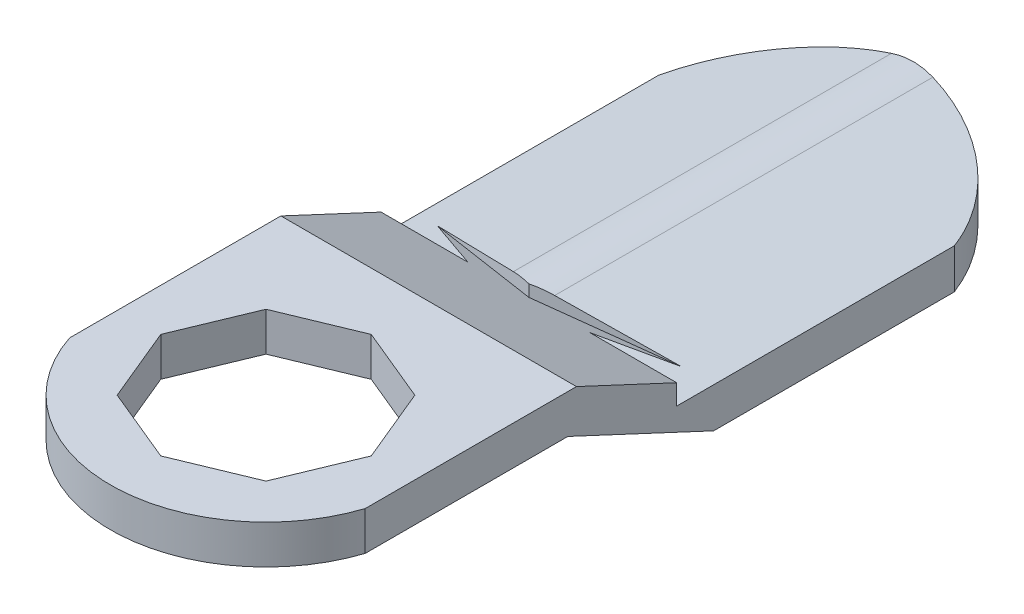
SolidWorks part; units mm, degrees
ref_plane "前视基准面" through (0, 0, 0) normal (0, 0, 1) x (1, 0, 0)
ref_plane "上视基准面" through (0, 0, 0) normal (0, 1, 0) x (1, 0, 0)
ref_plane "右视基准面" through (0, 0, 0) normal (1, 0, 0) x (0, 0, -1)
sketch "草图1" plane through (0, 0, 0) normal (0, 1, 0) x (1, 0, 0)
  line L0 (0, 33.2521) -> (0, -38.6616) construction
  line L1 (-19.8522, 0) -> (15.9092, 0) construction
  line L2 (0, 5.412) -> (-3.8268, 3.8268)
  line L3 (-3.8268, 3.8268) -> (-5.412, 0)
  line L4 (-5.412, 0) -> (-3.8268, -3.8268)
  line L5 (-3.8268, -3.8268) -> (0, -5.412)
  line L6 (0, -5.412) -> (3.8268, -3.8268)
  line L7 (3.8268, -3.8268) -> (5.412, 0)
  line L8 (5.412, 0) -> (3.8268, 3.8268)
  line L9 (3.8268, 3.8268) -> (0, 5.412)
  line L10 (-7.6, -2.498) -> (-7.6, 7.9206)
  line L11 (7.6, -2.498) -> (7.6, 7.9206)
  line L12 (-12.2442, -8) -> (14.4757, -8) construction
  line L13 (-14.231, 9.5) -> (17.6054, 9.5) construction
  circle A0 centre (0, 0) radius 5 construction
  arc A1 (7.6, -2.498) -> (-7.6, -2.498) centre (0, 0) cw
  arc A2 (7.6, 7.9206) -> (-7.6, 7.9206) centre (0, -9.5756) ccw
  dimension "D1" = 10
  dimension "D3" = 8
  dimension "D2" = 15.2
  dimension "D4" = 17.5
extrude "凸台-拉伸1" add sketch "草图1" along normal blind 2
sketch "草图3" plane through (0, 2, 0) normal (0, 1, 0) x (1, 0, 0)
  line L0 (-7.6, 7.9206) -> (-7.6, 15.4206)
  line L1 (-7.6, 15.4206) -> (0, 13.5178)
  line L2 (0, -2.2394) -> (0, 20.3405) construction
  line L3 (7.6, 15.4206) -> (0, 13.5178)
  line L4 (7.6, 7.9206) -> (7.6, 15.4206)
  arc A0 (7.6, 7.9206) -> (-7.6, 7.9206) centre (0, -9.5756) ccw construction
  arc A1 (7.6, 7.9206) -> (-7.6, 7.9206) centre (0, -9.5756) ccw
  dimension "D1" = 7.5
extrude "凸台-拉伸2" add sketch "草图3" against normal blind 8
sketch "草图4" plane through (7.6, 0, 0) normal (1, 0, 0) x (0, 0, -1)
  line L0 (8.3643, 2) -> (15.4206, -1.2929)
  line L1 (-2.498, 2) -> (15.4206, 2) construction
  line L3 (15.4206, -1.2929) -> (15.4206, -3.5)
  line L4 (15.4206, -3.5) -> (7.9206, 0)
  line L5 (15.4206, -6) -> (15.4206, 2) construction
  dimension "D1" = 2
  dimension "D2" = 5.5
extrude "切除-拉伸1" cut sketch "草图4" against normal through all and the other way through all
sketch "草图5" plane through (0, 2, 0) normal (0, 1, 0) x (1, 0, 0)
  line L0 (-7.6, 15.4206) -> (-7.6, 27.798)
  line L1 (-18.4795, 14.2131) -> (16.9599, 14.2131) construction
  line L2 (0, -10.618) -> (0, 36.9986) construction
  line L3 (-13.3383, 33.3) -> (9.3441, 33.3) construction
  line L4 (-16.4955, -8) -> (13.444, -8) construction
  line L5 (7.6, 15.4206) -> (7.6, 27.798)
  line L6 (-7.6, 15.4206) -> (0, 13.5178) construction
  line L7 (0, 13.5178) -> (7.6, 15.4206) construction
  line L8 (-7.6, 15.4206) -> (0, 13.5178)
  line L9 (0, 13.5178) -> (7.6, 15.4206)
  arc A0 (7.6, 27.798) -> (-7.6, 27.798) centre (0, 25.3) ccw
  arc A1 (-7.6, -2.498) -> (7.6, -2.498) centre (0, 0) ccw construction
  dimension "D1" = 41.3
extrude "凸台-拉伸3" add sketch "草图5" against normal up to vertex (5.5 mm away) up to point (7.6, -3.5, -15.4206)
ref_plane "基准面1" through (0, 0, -35) normal (0, 0, 1) x (1, 0, 0)
sketch "草图6" plane through (0, 0, -35) normal (0, 0, 1) x (1, 0, 0)
  line L0 (0, 4.0634) -> (0, -5.1191) construction
  line L1 (7.6, -1.4464) -> (1.0627, 0.0778)
  line L2 (9.4559, 0.2) -> (-12.5549, 0.2) construction
  line L4 (7.6, -3.5) -> (7.6, 2) construction
  line L5 (-7.6, -1.4464) -> (-1.0627, 0.0778)
  line L6 (7.6, -3.5) -> (0.6085, -1.87)
  line L7 (-7.6, -3.5) -> (-0.6085, -1.87)
  line L8 (7.2025, -3.4073) -> (0.6085, -1.87) construction
  line L9 (-7.1459, -3.3941) -> (-0.6085, -1.87) construction
  line L10 (-7.6, -3.5) -> (-7.6, 2) construction
  line L11 (-7.6, -3.5) -> (7.6, -3.5) construction
  line L12 (7.6566, -1.4596) -> (1.0627, 0.0778) construction
  line L13 (7.6, -1.4464) -> (7.6, -3.5)
  line L14 (-7.6, -1.4464) -> (-7.6, -3.5)
  arc A0 (1.0627, 0.0778) -> (-1.0627, 0.0778) centre (0, -4.4802) ccw
  arc A1 (0.6085, -1.87) -> (-0.6085, -1.87) centre (0, -4.4802) ccw
  dimension "D1" = 3.7
  dimension "D2" = 2
extrude "切除-拉伸2" cut sketch "草图6" along normal up to vertex flip side to cut
